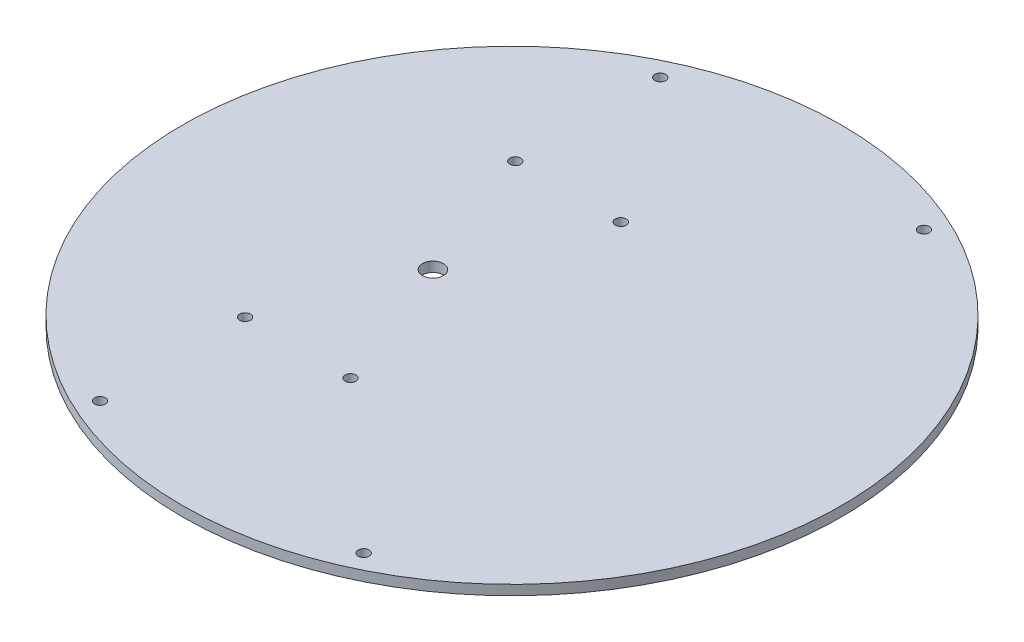
SolidWorks part; units mm, degrees
ref_plane "Alzado" through (0, 0, 0) normal (0, 0, 1) x (1, 0, 0)
ref_plane "Planta" through (0, 0, 0) normal (0, 1, 0) x (1, 0, 0)
ref_plane "Vista lateral" through (0, 0, 0) normal (1, 0, 0) x (0, 0, -1)
sketch "Croquis1" plane through (0, 0, 0) normal (0, 1, 0) x (1, 0, 0)
  circle A15 centre (40, -85) radius 1.65
  circle A16 centre (40, 85) radius 1.65
  circle A19 centre (0, 0) radius 100
  circle A25 centre (-40, -85) radius 1.65
  circle A28 centre (-40, 85) radius 1.65
  circle A29 centre (-40, 41) radius 1.65
  circle A30 centre (-40, -41) radius 1.65
  circle A31 centre (-24, 0) radius 3.175
  circle A32 centre (-8, 41) radius 1.65
  circle A33 centre (-8, -41) radius 1.65
  point P17 (0, 0)
  point P72 (0, 0)
  dimension "D10" = 200
  dimension "D14" = 41
  dimension "D3" = 40
  dimension "D7" = 3.3
  dimension "D13" = 24
  dimension "D16" = 41
  dimension "D2" = 85
  dimension "D18" = 8
  dimension "D5" = 40
  dimension "D12" = 6.35
  dimension "D4" = 85
  dimension "D6" = 40
  dimension "D8" = 40
  dimension "D9" = 85
  dimension "D11" = 85
  dimension "D15" = 41
  dimension "D17" = 41
extrude "Saliente-Extruir1" add sketch "Croquis1" along normal blind 3
